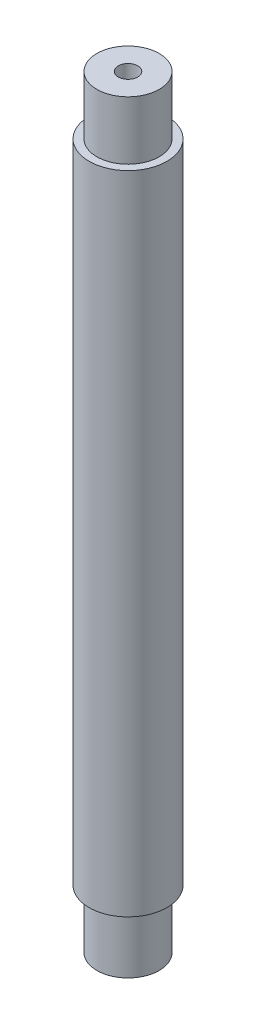
SolidWorks part; units mm, degrees
ref_plane "Płaszczyzna przednia" through (0, 0, 0) normal (0, 0, 1) x (1, 0, 0)
ref_plane "Płaszczyzna górna" through (0, 0, 0) normal (0, 1, 0) x (1, 0, 0)
ref_plane "Płaszczyzna prawa" through (0, 0, 0) normal (1, 0, 0) x (0, 0, -1)
sketch "Szkic1" plane through (0, 0, 0) normal (0, 0, 1) x (1, 0, 0)
  line L0 (0, 0) -> (0, 196)
  line L1 (0, 0) -> (8, 0)
  line L2 (8, 0) -> (8, 15)
  line L3 (8, 15) -> (10, 15)
  line L4 (10, 15) -> (10, 181)
  line L5 (10, 181) -> (8, 181)
  line L6 (8, 181) -> (8, 196)
  line L7 (8, 196) -> (0, 196)
  line L8 (2.5, 196) -> (2.5, 178)
  line L9 (2.5, 178) -> (8, 178)
  line L10 (8, 178) -> (8, 18)
  line L11 (8, 18) -> (0, 18)
  point P11 (0, 0)
  point P15 (8, 175.678)
  dimension "D1" = 160
  dimension "D2" = 10
  dimension "D3" = 8
  dimension "D4" = 8
  dimension "D5" = 15
  dimension "D6" = 15
  dimension "D7" = 3
  dimension "D8" = 2.5
  dimension "D9" = 3
revolve "Obrót1" add sketch "Szkic1" angle 360 about L0
